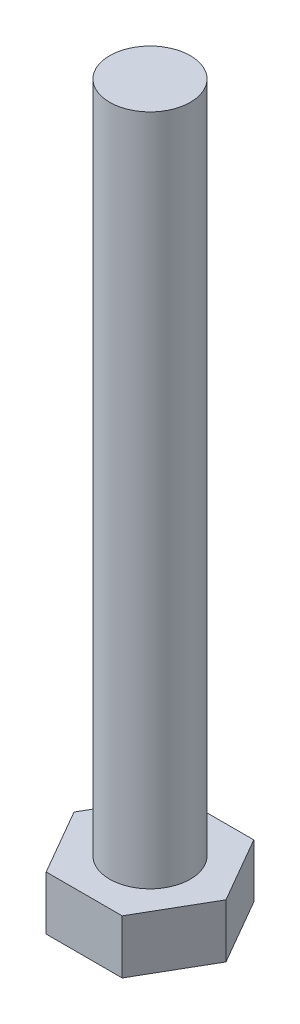
SolidWorks part; units mm, degrees
material "ABS"
ref_plane "Front" through (0, 0, 0) normal (0, 0, 1) x (1, 0, 0)
ref_plane "Top" through (0, 0, 0) normal (0, 1, 0) x (1, 0, 0)
ref_plane "Right" through (0, 0, 0) normal (1, 0, 0) x (0, 0, -1)
sketch "Sketch1" plane through (0, 0, 0) normal (0, 1, 0) x (1, 0, 0)
  line L1 (2.8232, -4.89) -> (5.6465, 0)
  line L2 (5.6465, 0) -> (2.8232, 4.89)
  line L3 (2.8232, 4.89) -> (-2.8232, 4.89)
  line L4 (-2.8232, 4.89) -> (-5.6465, 0)
  line L5 (-5.6465, 0) -> (-2.8232, -4.89)
  line L6 (-2.8232, -4.89) -> (2.8232, -4.89)
  circle A0 centre (0, 0) radius 4.89 construction
  dimension "D1" = 9.78
extrude "Boss-Extrude1" add sketch "Sketch1" along normal blind 4
sketch "Sketch2" plane through (0, 4, 0) normal (0, 1, 0) x (1, 0, 0)
  circle A0 centre (0, 0) radius 3
  dimension "D1" = 6
extrude "Boss-Extrude2" add sketch "Sketch2" along normal blind 50
